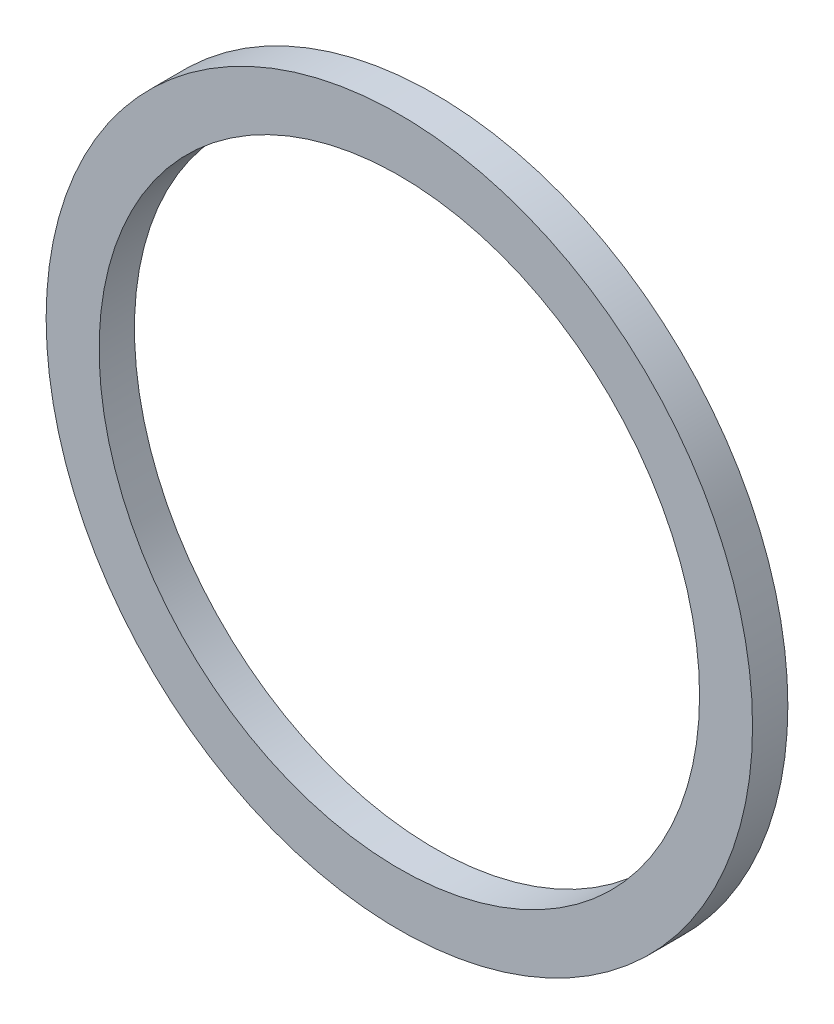
SolidWorks part; units mm, degrees
ref_plane "Plan de face" through (0, 0, 0) normal (0, 0, 1) x (1, 0, 0)
ref_plane "Plan de dessus" through (0, 0, 0) normal (0, 1, 0) x (1, 0, 0)
ref_plane "Plan de droite" through (0, 0, 0) normal (1, 0, 0) x (0, 0, -1)
sketch "Esquisse1" plane through (0, 0, 0) normal (0, 0, 1) x (1, 0, 0)
  circle A0 centre (0, 0) radius 8.5
  circle A1 centre (0, 0) radius 10
  dimension "D1" = 17
  dimension "D2" = 20
extrude "Boss.-Extru.1" add sketch "Esquisse1" along normal blind 1
